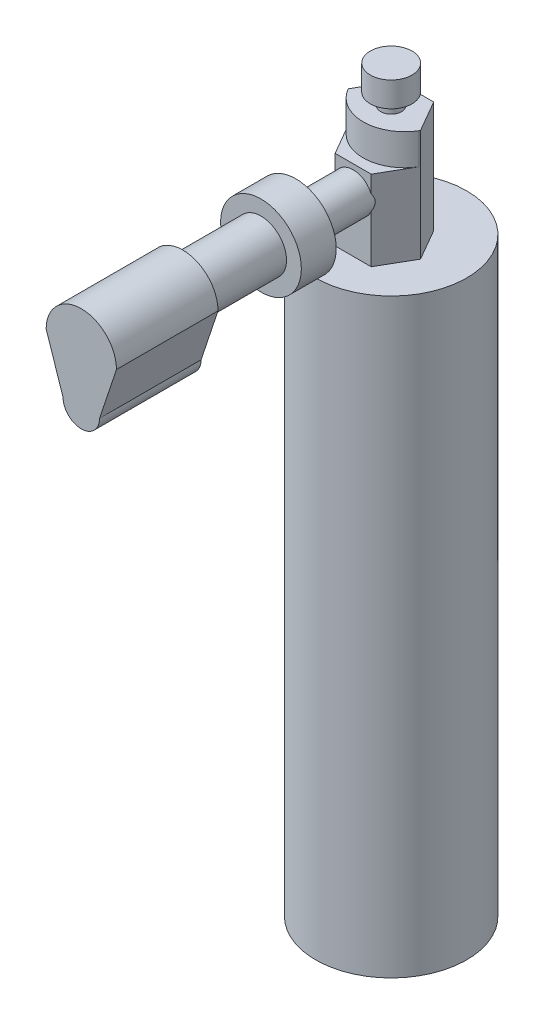
SolidWorks part; units mm, degrees
ref_plane "Front Plane" through (0, 0, 0) normal (0, 0, 1) x (1, 0, 0)
ref_plane "Top Plane" through (0, 0, 0) normal (0, 1, 0) x (1, 0, 0)
ref_plane "Right Plane" through (0, 0, 0) normal (1, 0, 0) x (0, 0, -1)
sketch "Sketch1" plane through (0, 0, 0) normal (0, 1, 0) x (1, 0, 0)
  circle A0 centre (0, 0) radius 14.5
  dimension "D1" = 29
extrude "Boss-Extrude1" add sketch "Sketch1" along normal blind 113.4
sketch "Sketch2" plane through (0, 113.4, 0) normal (0, 1, 0) x (1, 0, 0)
  circle A0 centre (0, 0) radius 2
  dimension "D1" = 4
extrude "Boss-Extrude2" add sketch "Sketch2" along normal blind 28.5
sketch "Sketch3" plane through (0, 141.9, 0) normal (0, 1, 0) x (1, 0, 0)
  circle A0 centre (0, 0) radius 4
  dimension "D1" = 8
extrude "Boss-Extrude3" add sketch "Sketch3" against normal blind 4.8
sketch "Sketch4" plane through (0, 113.4, 0) normal (0, 1, 0) x (1, 0, 0)
  line L3 (3.4641, 4.7) -> (-3.4641, 4.7)
  line L4 (-3.4641, 4.7) -> (-6.9282, -1.3)
  line L5 (-6.9282, -1.3) -> (-3.4641, -7.3)
  line L6 (-3.4641, -7.3) -> (3.4641, -7.3)
  line L7 (3.4641, -7.3) -> (6.9282, -1.3)
  line L8 (6.9282, -1.3) -> (3.4641, 4.7)
  circle A0 centre (0, 0) radius 14.5 construction
  circle A1 centre (0, -1.3) radius 6.9282 construction
  circle A4 centre (0, 0) radius 14.5 construction
  dimension "D1" = 12
  dimension "D2" = 4.7
extrude "Boss-Extrude4" add sketch "Sketch4" along normal blind 21.4
sketch "Sketch6" plane through (0, 134.8, 0) normal (0, 1, 0) x (1, 0, 0)
  line L4 (-6.9282, -1.3) -> (-6.9282, -9.4658)
  line L5 (-6.9282, -9.4658) -> (6.9282, -9.4658)
  line L6 (6.9282, -1.3) -> (6.9282, -9.4658)
  arc A0 (-6.9282, -1.3) -> (6.9282, -1.3) centre (0, 2.5618) ccw
extrude "Cut-Extrude1" cut sketch "Sketch6" against normal blind 6
sketch "Sketch7" plane through (0, 0, 7.3) normal (0, 0, 1) x (1, 0, 0)
  line L0 (-3.4641, 128.8) -> (3.4641, 128.8) construction
  circle A0 centre (0, 124.05) radius 3.75
  dimension "D1" = 7.5
  dimension "D2" = 4.75
extrude "Boss-Extrude5" add sketch "Sketch7" along normal blind 11 and the other way blind 2
sketch "Sketch8" plane through (0, 0, 18.3) normal (0, 0, 1) x (1, 0, 0)
  circle A0 centre (0, 124.05) radius 7.75
  dimension "D1" = 15.5
extrude "Boss-Extrude6" add sketch "Sketch8" along normal blind 6.7
sketch "Sketch9" plane through (0, 0, 25) normal (0, 0, 1) x (1, 0, 0)
  circle A0 centre (0, 124.05) radius 4.9
  dimension "D1" = 9.8
extrude "Boss-Extrude7" add sketch "Sketch9" along normal blind 15
sketch "Sketch10" plane through (0, 0, 40) normal (0, 0, 1) x (1, 0, 0)
  line L0 (0, 117.8) -> (0, 110.8) construction
  line L1 (-6.75, 124.05) -> (-3.5, 114.3)
  line L2 (3.5, 114.3) -> (6.75, 124.05)
  arc A0 (6.75, 124.05) -> (-6.75, 124.05) centre (0, 124.05) ccw
  arc A1 (-3.5, 114.3) -> (3.5, 114.3) centre (0, 114.3) ccw
  dimension "D1" = 13.5
  dimension "D2" = 7
extrude "Boss-Extrude8" add sketch "Sketch10" along normal blind 19.5
sketch "Sketch11" plane through (0, 141.9, 0) normal (0, 1, 0) x (1, 0, 0)
  line L0 (0, 4) -> (0.2732, 3.6147)
  line L1 (0, 4) -> (0, 3.625) construction
  line L2 (0, 4) -> (-0.2732, 3.6147)
  line L3 (0.6106, 3.9531) -> (0.8217, 3.5306)
  line L4 (0.6106, 3.9531) -> (0.2818, 3.614)
  line L5 (1.2069, 3.8136) -> (1.351, 3.3638)
  line L6 (1.2069, 3.8136) -> (0.8302, 3.5287)
  line L7 (1.7749, 3.5847) -> (1.8487, 3.1182)
  line L8 (1.7749, 3.5847) -> (1.3591, 3.3606)
  line L9 (2.3013, 3.2717) -> (2.303, 2.7994)
  line L10 (2.3013, 3.2717) -> (1.8562, 3.1137)
  line L11 (2.7737, 2.8821) -> (2.7034, 2.4151)
  line L12 (2.7737, 2.8821) -> (2.3097, 2.7939)
  line L13 (3.1812, 2.4249) -> (3.0403, 1.9741)
  line L14 (3.1812, 2.4249) -> (2.7091, 2.4086)
  line L15 (3.514, 1.9109) -> (3.306, 1.4868)
  line L16 (3.514, 1.9109) -> (3.0451, 1.9668)
  line L17 (3.7646, 1.3521) -> (3.4943, 0.9648)
  line L18 (3.7646, 1.3521) -> (3.3096, 1.4789)
  line L19 (3.9268, 0.7616) -> (3.6006, 0.4201)
  line L20 (3.9268, 0.7616) -> (3.4966, 0.9564)
  line L21 (3.9971, 0.1532) -> (3.6225, -0.1345)
  line L22 (3.9971, 0.1532) -> (3.6016, 0.4114)
  line L23 (3.9736, -0.4587) -> (3.5595, -0.6859)
  line L24 (3.9736, -0.4587) -> (3.6222, -0.1432)
  line L25 (3.857, -1.0599) -> (3.4131, -1.2212)
  line L26 (3.857, -1.0599) -> (3.5579, -0.6944)
  line L27 (3.65, -1.6363) -> (3.1867, -1.7279)
  line L28 (3.65, -1.6363) -> (3.4102, -1.2294)
  line L29 (3.3575, -2.1743) -> (2.8856, -2.1941)
  line L30 (3.3575, -2.1743) -> (3.1825, -1.7356)
  line L31 (2.9862, -2.6613) -> (2.5168, -2.6089)
  line L32 (2.9862, -2.6613) -> (2.8803, -2.201)
  line L33 (2.545, -3.086) -> (2.0891, -2.9625)
  line L34 (2.545, -3.086) -> (2.5106, -2.6149)
  line L35 (2.0441, -3.4383) -> (1.6124, -3.2467)
  line L36 (2.0441, -3.4383) -> (2.082, -2.9675)
  line L37 (1.4953, -3.71) -> (1.0979, -3.4547)
  line L38 (1.4953, -3.71) -> (1.6046, -3.2505)
  line L39 (0.9114, -3.8948) -> (0.5577, -3.5818)
  line L40 (0.9114, -3.8948) -> (1.0896, -3.4574)
  line L41 (0.3062, -3.9883) -> (0.0044, -3.625)
  line L42 (0.3062, -3.9883) -> (0.5491, -3.5832)
  line L43 (-0.3062, -3.9883) -> (-0.5491, -3.5832)
  line L44 (-0.3062, -3.9883) -> (-0.0044, -3.625)
  line L45 (-0.9114, -3.8948) -> (-1.0896, -3.4574)
  line L46 (-0.9114, -3.8948) -> (-0.5577, -3.5818)
  line L47 (-1.4953, -3.71) -> (-1.6046, -3.2505)
  line L48 (-1.4953, -3.71) -> (-1.0979, -3.4547)
  line L49 (-2.0441, -3.4383) -> (-2.082, -2.9675)
  line L50 (-2.0441, -3.4383) -> (-1.6124, -3.2467)
  line L51 (-2.545, -3.086) -> (-2.5106, -2.6149)
  line L52 (-2.545, -3.086) -> (-2.0891, -2.9625)
  line L53 (-2.9862, -2.6613) -> (-2.8803, -2.201)
  line L54 (-2.9862, -2.6613) -> (-2.5168, -2.6089)
  line L55 (-3.3575, -2.1743) -> (-3.1825, -1.7356)
  line L56 (-3.3575, -2.1743) -> (-2.8856, -2.1941)
  line L57 (-3.65, -1.6363) -> (-3.4102, -1.2294)
  line L58 (-3.65, -1.6363) -> (-3.1867, -1.7279)
  line L59 (-3.857, -1.0599) -> (-3.5579, -0.6944)
  line L60 (-3.857, -1.0599) -> (-3.4131, -1.2212)
  line L61 (-3.9736, -0.4587) -> (-3.6222, -0.1432)
  line L62 (-3.9736, -0.4587) -> (-3.5595, -0.6859)
  line L63 (-3.9971, 0.1532) -> (-3.6016, 0.4114)
  line L64 (-3.9971, 0.1532) -> (-3.6225, -0.1345)
  line L65 (-3.9268, 0.7616) -> (-3.4966, 0.9564)
  line L66 (-3.9268, 0.7616) -> (-3.6006, 0.4201)
  line L67 (-3.7646, 1.3521) -> (-3.3096, 1.4789)
  line L68 (-3.7646, 1.3521) -> (-3.4943, 0.9648)
  line L69 (-3.514, 1.9109) -> (-3.0451, 1.9668)
  line L70 (-3.514, 1.9109) -> (-3.306, 1.4868)
  line L71 (-3.1812, 2.4249) -> (-2.7091, 2.4086)
  line L72 (-3.1812, 2.4249) -> (-3.0403, 1.9741)
  line L73 (-2.7737, 2.8821) -> (-2.3097, 2.7939)
  line L74 (-2.7737, 2.8821) -> (-2.7034, 2.4151)
  line L75 (-2.3013, 3.2717) -> (-1.8562, 3.1137)
  line L76 (-2.3013, 3.2717) -> (-2.303, 2.7994)
  line L77 (-1.7749, 3.5847) -> (-1.3591, 3.3606)
  line L78 (-1.7749, 3.5847) -> (-1.8487, 3.1182)
  line L79 (-1.2069, 3.8136) -> (-0.8302, 3.5287)
  line L80 (-1.2069, 3.8136) -> (-1.351, 3.3638)
  line L81 (-0.6106, 3.9531) -> (-0.2818, 3.614)
  line L82 (-0.6106, 3.9531) -> (-0.8217, 3.5306)
  arc A0 (-0.2732, 3.6147) -> (-0.2818, 3.614) centre (0, 0) ccw construction
  circle A1 centre (0, 0) radius 4 construction
  circle A2 centre (0, 0) radius 4
  arc A3 (0.2818, 3.614) -> (0.2732, 3.6147) centre (0, 0) ccw
  arc A4 (0.2818, 3.614) -> (0.2732, 3.6147) centre (0, 0) ccw construction
  arc A5 (0.8302, 3.5287) -> (0.8217, 3.5306) centre (0, 0) ccw construction
  arc A6 (0.8302, 3.5287) -> (0.8217, 3.5306) centre (0, 0) ccw
  arc A7 (1.3591, 3.3606) -> (1.351, 3.3638) centre (0, 0) ccw construction
  arc A8 (1.3591, 3.3606) -> (1.351, 3.3638) centre (0, 0) ccw
  arc A9 (-0.2732, 3.6147) -> (-0.2818, 3.614) centre (0, 0) ccw
  arc A10 (-0.8217, 3.5306) -> (-0.8302, 3.5287) centre (0, 0) ccw construction
  arc A11 (-0.8217, 3.5306) -> (-0.8302, 3.5287) centre (0, 0) ccw
  arc A12 (-1.351, 3.3638) -> (-1.3591, 3.3606) centre (0, 0) ccw construction
  arc A13 (-1.351, 3.3638) -> (-1.3591, 3.3606) centre (0, 0) ccw
  arc A14 (-1.8487, 3.1182) -> (-1.8562, 3.1137) centre (0, 0) ccw construction
  arc A15 (-1.8487, 3.1182) -> (-1.8562, 3.1137) centre (0, 0) ccw
  arc A16 (1.8562, 3.1137) -> (1.8487, 3.1182) centre (0, 0) ccw construction
  arc A17 (1.8562, 3.1137) -> (1.8487, 3.1182) centre (0, 0) ccw
  arc A18 (2.3097, 2.7939) -> (2.303, 2.7994) centre (0, 0) ccw construction
  arc A19 (2.3097, 2.7939) -> (2.303, 2.7994) centre (0, 0) ccw
  arc A20 (2.7091, 2.4086) -> (2.7034, 2.4151) centre (0, 0) ccw construction
  arc A21 (2.7091, 2.4086) -> (2.7034, 2.4151) centre (0, 0) ccw
  arc A22 (3.0451, 1.9668) -> (3.0403, 1.9741) centre (0, 0) ccw construction
  arc A23 (3.0451, 1.9668) -> (3.0403, 1.9741) centre (0, 0) ccw
  arc A24 (3.3096, 1.4789) -> (3.306, 1.4868) centre (0, 0) ccw construction
  arc A25 (3.3096, 1.4789) -> (3.306, 1.4868) centre (0, 0) ccw
  arc A26 (3.4966, 0.9564) -> (3.4943, 0.9648) centre (0, 0) ccw construction
  arc A27 (3.4966, 0.9564) -> (3.4943, 0.9648) centre (0, 0) ccw
  arc A28 (3.6016, 0.4114) -> (3.6006, 0.4201) centre (0, 0) ccw construction
  arc A29 (3.6016, 0.4114) -> (3.6006, 0.4201) centre (0, 0) ccw
  arc A30 (3.6222, -0.1432) -> (3.6225, -0.1345) centre (0, 0) ccw construction
  arc A31 (3.6222, -0.1432) -> (3.6225, -0.1345) centre (0, 0) ccw
  arc A32 (3.5579, -0.6944) -> (3.5595, -0.6859) centre (0, 0) ccw construction
  arc A33 (3.5579, -0.6944) -> (3.5595, -0.6859) centre (0, 0) ccw
  arc A34 (3.4102, -1.2294) -> (3.4131, -1.2212) centre (0, 0) ccw construction
  arc A35 (3.4102, -1.2294) -> (3.4131, -1.2212) centre (0, 0) ccw
  arc A36 (3.1825, -1.7356) -> (3.1867, -1.7279) centre (0, 0) ccw construction
  arc A37 (3.1825, -1.7356) -> (3.1867, -1.7279) centre (0, 0) ccw
  arc A38 (2.8803, -2.201) -> (2.8856, -2.1941) centre (0, 0) ccw construction
  arc A39 (2.8803, -2.201) -> (2.8856, -2.1941) centre (0, 0) ccw
  arc A40 (2.5106, -2.6149) -> (2.5168, -2.6089) centre (0, 0) ccw construction
  arc A41 (2.5106, -2.6149) -> (2.5168, -2.6089) centre (0, 0) ccw
  arc A42 (2.082, -2.9675) -> (2.0891, -2.9625) centre (0, 0) ccw construction
  arc A43 (2.082, -2.9675) -> (2.0891, -2.9625) centre (0, 0) ccw
  arc A44 (1.6046, -3.2505) -> (1.6124, -3.2467) centre (0, 0) ccw construction
  arc A45 (1.6046, -3.2505) -> (1.6124, -3.2467) centre (0, 0) ccw
  arc A46 (1.0896, -3.4574) -> (1.0979, -3.4547) centre (0, 0) ccw construction
  arc A47 (1.0896, -3.4574) -> (1.0979, -3.4547) centre (0, 0) ccw
  arc A48 (0.5491, -3.5832) -> (0.5577, -3.5818) centre (0, 0) ccw construction
  arc A49 (0.5491, -3.5832) -> (0.5577, -3.5818) centre (0, 0) ccw
  arc A50 (-0.0044, -3.625) -> (0.0044, -3.625) centre (0, 0) ccw construction
  arc A51 (-0.5577, -3.5818) -> (-0.5491, -3.5832) centre (0, 0) ccw construction
  arc A52 (-0.5577, -3.5818) -> (-0.5491, -3.5832) centre (0, 0) ccw
  arc A53 (-0.0044, -3.625) -> (0.0044, -3.625) centre (0, 0) ccw
  arc A54 (-1.0979, -3.4547) -> (-1.0896, -3.4574) centre (0, 0) ccw construction
  arc A55 (-1.0979, -3.4547) -> (-1.0896, -3.4574) centre (0, 0) ccw
  arc A56 (-1.6124, -3.2467) -> (-1.6046, -3.2505) centre (0, 0) ccw construction
  arc A57 (-1.6124, -3.2467) -> (-1.6046, -3.2505) centre (0, 0) ccw
  arc A58 (-2.0891, -2.9625) -> (-2.082, -2.9675) centre (0, 0) ccw construction
  arc A59 (-2.0891, -2.9625) -> (-2.082, -2.9675) centre (0, 0) ccw
  arc A60 (-2.5168, -2.6089) -> (-2.5106, -2.6149) centre (0, 0) ccw construction
  arc A61 (-2.5168, -2.6089) -> (-2.5106, -2.6149) centre (0, 0) ccw
  arc A62 (-2.8856, -2.1941) -> (-2.8803, -2.201) centre (0, 0) ccw construction
  arc A63 (-2.8856, -2.1941) -> (-2.8803, -2.201) centre (0, 0) ccw
  arc A64 (-3.1867, -1.7279) -> (-3.1825, -1.7356) centre (0, 0) ccw construction
  arc A65 (-3.1867, -1.7279) -> (-3.1825, -1.7356) centre (0, 0) ccw
  arc A66 (-3.4131, -1.2212) -> (-3.4102, -1.2294) centre (0, 0) ccw construction
  arc A67 (-3.4131, -1.2212) -> (-3.4102, -1.2294) centre (0, 0) ccw
  arc A68 (-3.5595, -0.6859) -> (-3.5579, -0.6944) centre (0, 0) ccw construction
  arc A69 (-3.5595, -0.6859) -> (-3.5579, -0.6944) centre (0, 0) ccw
  arc A70 (-3.6225, -0.1345) -> (-3.6222, -0.1432) centre (0, 0) ccw construction
  arc A71 (-3.6225, -0.1345) -> (-3.6222, -0.1432) centre (0, 0) ccw
  arc A72 (-3.6006, 0.4201) -> (-3.6016, 0.4114) centre (0, 0) ccw construction
  arc A73 (-3.6006, 0.4201) -> (-3.6016, 0.4114) centre (0, 0) ccw
  arc A74 (-3.4943, 0.9648) -> (-3.4966, 0.9564) centre (0, 0) ccw construction
  arc A75 (-3.4943, 0.9648) -> (-3.4966, 0.9564) centre (0, 0) ccw
  arc A76 (-3.306, 1.4868) -> (-3.3096, 1.4789) centre (0, 0) ccw construction
  arc A77 (-3.0403, 1.9741) -> (-3.0451, 1.9668) centre (0, 0) ccw construction
  arc A78 (-3.0403, 1.9741) -> (-3.0451, 1.9668) centre (0, 0) ccw
  arc A79 (-2.7034, 2.4151) -> (-2.7091, 2.4086) centre (0, 0) ccw construction
  arc A80 (-2.7034, 2.4151) -> (-2.7091, 2.4086) centre (0, 0) ccw
  arc A81 (-2.303, 2.7994) -> (-2.3097, 2.7939) centre (0, 0) ccw construction
  arc A82 (-2.303, 2.7994) -> (-2.3097, 2.7939) centre (0, 0) ccw
  arc A83 (-3.306, 1.4868) -> (-3.3096, 1.4789) centre (0, 0) ccw
  point P132 (0, 0)
  circle M1 centre (0, 0) radius 4
  dimension "D1" = 7.25
  dimension "D2" = 41
extrude "Cut-Extrude2" [suppressed] cut sketch "Sketch11" against normal up to surface (4.8 mm away) contours A3 L4 L0 M1 | A6 L6 L3 M1 | A8 L8 L5 M1 | A17 L10 L7 M1 | A19 L12 L9 M1 | A21 L14 L11 M1 | A23 L16 L13 M1 | A25 L18 L15 M1 | A27 L20 L17 M1 | A29 L22 L19 M1 | A31 L24 L21 M1 | A33 L26 L23 M1 | A35 L28 L25 M1 | A37 L30 L27 M1 | A39 L32 L29 M1 | A43 L36 L33 M1 | A41 L34 L31 M1 | A45 L38 L35 M1 | A47 L40 L37 M1 | A49 L42 L39 M1 | A53 L44 L41 M1 | A52 L46 L43 M1 | A55 L48 L45 M1 | A57 L50 L47 M1 | A59 L52 L49 M1 | A61 L54 L51 M1 | A63 L56 L53 M1 | A65 L58 L55 M1 | A67 L60 L57 M1 | A69 L62 L59 M1 | A71 L64 L61 M1 | A73 L66 L63 M1 | A75 L68 L65 M1 | A83 L70 L67 M1 | A78 L72 L69 M1 | A80 L74 L71 M1 | A9 L2 L81 M1 | A11 L82 L79 M1 | A13 L80 L77 M1 | A15 L78 L75 M1 | A82 L76 L73 M1
